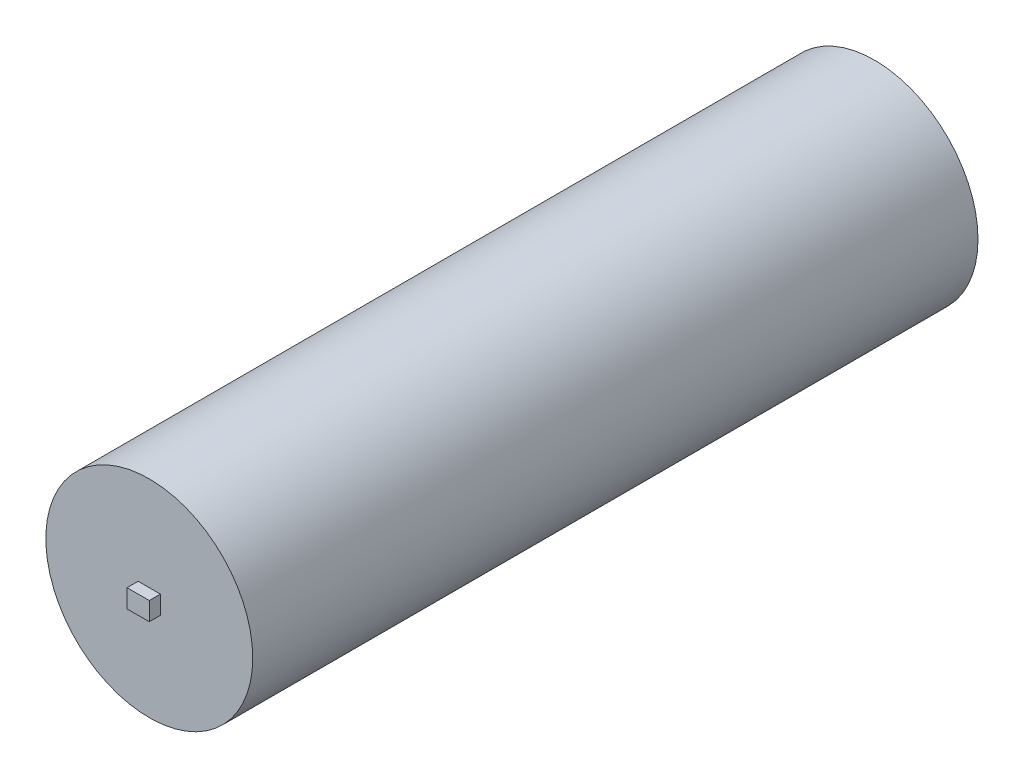
SolidWorks part; units mm, degrees
ref_plane "Front Plane" through (0, 0, 0) normal (0, 0, 1) x (1, 0, 0)
ref_plane "Top Plane" through (0, 0, 0) normal (0, 1, 0) x (1, 0, 0)
ref_plane "Right Plane" through (0, 0, 0) normal (1, 0, 0) x (0, 0, -1)
other "Центр тяжести"
sketch "Эскиз1" plane through (0, 0, 0) normal (0, 0, 1) x (1, 0, 0)
  circle A0 centre (0, 0) radius 9.3
  dimension "D1" = 18.6
extrude "Бобышка-Вытянуть1" add sketch "Эскиз1" along normal mid plane 65.2
sketch "Эскиз2" plane through (0, 0, 32.6) normal (0, 0, 1) x (1, 0, 0)
  line L1 (-1, -0.8259) -> (1, -0.8259)
  line L2 (-1, -0.8259) -> (-1, 0.8259)
  line L3 (-1, 0.8259) -> (1, 0.8259)
  line L4 (1, -0.8259) -> (1, 0.8259)
  line L5 (-1, -0.8259) -> (1, 0.8259) construction
  line L6 (-1, 0.8259) -> (1, -0.8259) construction
  point P0 (0, 0)
  dimension "D1" = 2
extrude "Бобышка-Вытянуть2" add sketch "Эскиз2" along normal blind 1
